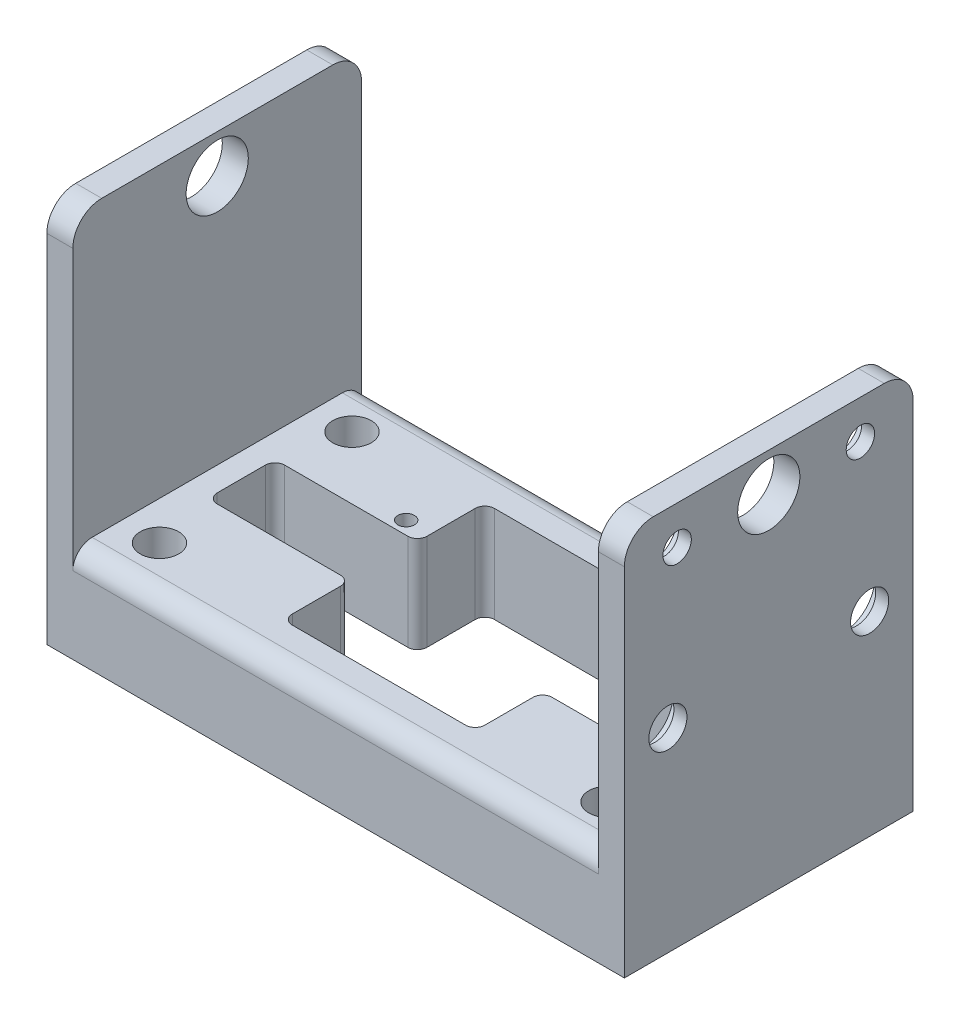
SolidWorks part; units mm, degrees
ref_plane "Front Plane" through (0, 0, 0) normal (0, 0, 1) x (1, 0, 0)
ref_plane "Top Plane" through (0, 0, 0) normal (0, 1, 0) x (1, 0, 0)
ref_plane "Right Plane" through (0, 0, 0) normal (1, 0, 0) x (0, 0, -1)
sketch "Sketch1" plane through (0, 0, 0) normal (0, 1, 0) x (1, 0, 0)
  line L1 (30, -15) -> (-30, -15)
  line L2 (30, -15) -> (30, 15)
  line L3 (30, 15) -> (-30, 15)
  line L4 (-30, -15) -> (-30, 15)
  line L5 (30, -15) -> (-30, 15) construction
  line L6 (30, 15) -> (-30, -15) construction
  point P0 (0, 0)
  dimension "D1" = 60
  dimension "D2" = 30
extrude "Boss-Extrude1" add sketch "Sketch1" along normal blind 10
sketch "Sketch2" plane through (0, 10, 0) normal (0, 1, 0) x (1, 0, 0)
  line L0 (-30, 0) -> (30, 0) construction
  line L1 (-30, 15) -> (-30, -15) construction
  line L2 (30, -15) -> (30, 15) construction
  line L8 (-27.3, -15) -> (-30, -15)
  line L9 (-27.3, -15) -> (-27.3, 15)
  line L10 (-27.3, 15) -> (-30, 15)
  line L11 (-30, -15) -> (-30, 15)
  line L12 (-27.3, -15) -> (-30, 15) construction
  line L13 (-27.3, 15) -> (-30, -15) construction
  point P6 (-28.65, 0)
  dimension "D1" = 2.7
extrude "Boss-Extrude2" add sketch "Sketch2" along normal blind 30
sketch "Sketch3" plane through (-27.3, 0, 0) normal (1, 0, 0) x (0, 0, -1)
  line L0 (0, 10) -> (0, 40) construction
  line L1 (-15, 10) -> (15, 10) construction
  line L2 (-15, 40) -> (15, 40) construction
  line L3 (-15, 40) -> (15, 40) construction
  line L10 (-15, 25) -> (15, 25) construction
  line L11 (-15, 40) -> (-15, 10) construction
  line L12 (15, 40) -> (15, 10) construction
  circle A0 centre (0, 36) radius 3.23
  dimension "D4" = 6.46
  dimension "D2" = 4
extrude "Cut-Extrude1" cut sketch "Sketch3" against normal up to next
fillet "Fillet1" radius 3 2 edges at (-28.65, 40, 15) (-28.65, 40, -15)
mirror "Mirror1" about plane through (0, 0, 0) normal (1, 0, 0) of "Fillet1", "Cut-Extrude1", "Boss-Extrude2"
fillet "Fillet4" radius 2 2 edges at (0, 10, 15) (0, 10, -15)
sketch "Sketch5" plane through (27.3, 0, 0) normal (-1, 0, 0) x (0, 0, 1)
  line L0 (13, 10) -> (-13, 10) construction
  line L1 (15, 37) -> (15, 8) construction
  line L2 (12, 40) -> (-12, 40) construction
  circle A0 centre (10.48, 20.25) radius 1.98
  circle A1 centre (9.52, 36) radius 1.475
  dimension "D1" = 3.96
  dimension "D2" = 10.25
  dimension "D3" = 4.52
  dimension "D4" = 2.95
  dimension "D5" = 5.48
  dimension "D6" = 4
extrude "Cut-Extrude3" cut sketch "Sketch5" against normal up to next
mirror "Mirror2" about plane through (0, 0, 0) normal (0, 0, 1) of "Cut-Extrude3"
sketch "Sketch6" plane through (0, 10, 0) normal (0, 1, 0) x (1, 0, 0)
  line L0 (27.3, -15) -> (-27.3, -15) construction
  line L1 (30, 12) -> (30, -12) construction
  line L2 (-30, 0) -> (30, 0) construction
  line L3 (-30, 12) -> (-30, -12) construction
  line L4 (0, 15) -> (0, -15) construction
  line L5 (-27.3, 15) -> (27.3, 15) construction
  line L6 (-24.8, -3.5) -> (-24.8, 3.5)
  line L7 (-24.8, 3.5) -> (-10, 3.5)
  line L8 (-10, 3.5) -> (-10, 10.5)
  line L9 (-10, 10.5) -> (10, 10.5)
  line L10 (10, 3.5) -> (10, 10.5)
  line L11 (24.8, 3.5) -> (10, 3.5)
  line L12 (24.8, -3.5) -> (24.8, 3.5)
  line L13 (24.8, -3.5) -> (10, -3.5)
  line L14 (10, -3.5) -> (10, -10.5)
  line L15 (-10, -10.5) -> (10, -10.5)
  line L16 (-10, -3.5) -> (-10, -10.5)
  line L17 (-24.8, -3.5) -> (-10, -3.5)
  line L18 (27.3, 13) -> (-27.3, 13) construction
  line L19 (27.3, -12) -> (27.3, 12) construction
  circle A0 centre (-12.53, 4.86) radius 0.86
  point P20 (0, 0)
  point P24 (24.8, 0)
  point P29 (-24.8, 0)
  point P30 (0, 0)
  point P34 (30, 0)
  point P37 (0, -4.7356)
  point P38 (-20.0496, 0)
  dimension "D1" = 1.72
  dimension "D2" = 4.86
  dimension "D3" = 12.53
  dimension "D4" = 3.5
  dimension "D5" = 10
  dimension "D6" = 2.5
  dimension "D7" = 2.5
extrude "Cut-Extrude4" cut sketch "Sketch6" against normal up to next
fillet "Fillet6" radius 1 12 edges at (24.8, 5, 3.5) (10, 5, 3.5) (10, 5, 10.5) (-10, 5, 10.5) (-10, 5, 3.5) (-24.8, 5, 3.5) (-24.8, 5, -3.5) (-10, 5, -3.5) (-10, 5, -10.5) (10, 5, -10.5) (10, 5, -3.5) (24.8, 5, -3.5)
sketch "Sketch7" plane through (27.3, 0, 0) normal (-1, 0, 0) x (0, 0, 1)
  line L0 (0, 40) -> (0, 10) construction
  line L1 (12, 40) -> (-12, 40) construction
  line L2 (13, 10) -> (-13, 10) construction
  circle A0 centre (-9.52, 36) radius 2.725
  circle A1 centre (-9.52, 36) radius 1.475 construction
  circle A2 centre (-10.48, 20.25) radius 3.23
  circle A3 centre (-10.48, 20.25) radius 1.98 construction
  circle A4 centre (10.48, 20.25) radius 3.23
  circle A5 centre (9.52, 36) radius 2.725
  dimension "D1" = 1.25
  dimension "D2" = 1.25
extrude "Cut-Extrude5" cut sketch "Sketch7" against normal blind 1.35
sketch "Sketch8" plane through (0, 10, 0) normal (0, 1, 0) x (1, 0, 0)
  line L0 (-23.3, 13) -> (-23.3, -13) construction
  line L1 (27.3, 13) -> (-27.3, 13) construction
  line L2 (-27.3, -13) -> (27.3, -13) construction
  line L3 (-27.3, -12) -> (-27.3, 12) construction
  circle A0 centre (-23.3, 10) radius 2
  circle A1 centre (-23.3, -10) radius 2
  point P10 (-23.8627, 9.4366)
  point P11 (-23.3707, -9.137)
  dimension "D2" = 4
  dimension "D3" = 4
  dimension "D5" = 3
  dimension "D1" = 4
  dimension "D4" = 3
extrude "Cut-Extrude6" cut sketch "Sketch8" against normal blind 3
sketch "Sketch9" plane through (0, 10, 0) normal (0, 1, 0) x (1, 0, 0)
  circle A0 centre (-23.3, 10) radius 1
  circle A1 centre (-23.3, -10) radius 1
  dimension "D1" = 2
  dimension "D2" = 2
extrude "Cut-Extrude7" cut sketch "Sketch9" against normal up to next
mirror "Mirror3" about plane through (0, 0, 0) normal (1, 0, 0) of "Cut-Extrude7", "Cut-Extrude6"
